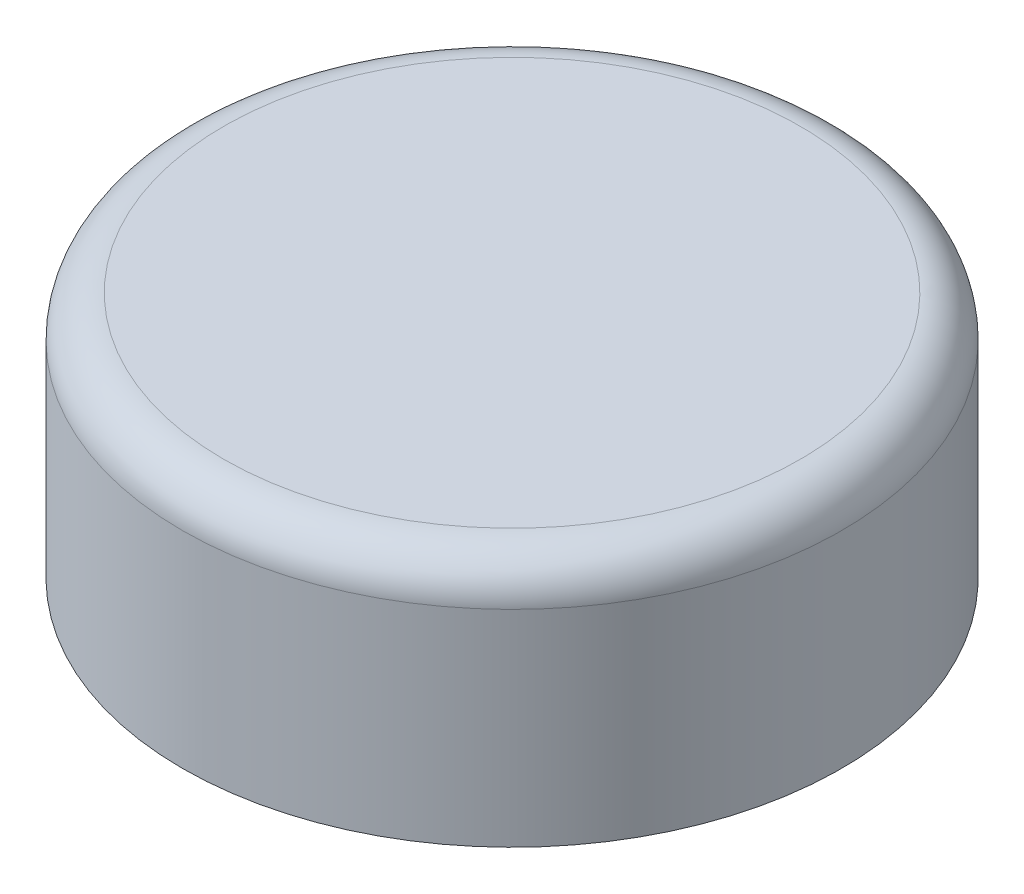
SolidWorks part; units mm, degrees
ref_plane "Front Plane" through (0, 0, 0) normal (0, 0, 1) x (1, 0, 0)
ref_plane "Top Plane" through (0, 0, 0) normal (0, 1, 0) x (1, 0, 0)
ref_plane "Right Plane" through (0, 0, 0) normal (1, 0, 0) x (0, 0, -1)
sketch "Sketch1" plane through (0, 0, 0) normal (0, 1, 0) x (1, 0, 0)
  circle A0 centre (0, 0) radius 40
  circle A1 centre (0, 0) radius 36
extrude "Boss-Extrude1" add sketch "Sketch1" along normal blind 30 contours A0
fillet "Fillet1" radius 5 1 edges at (0, 30, 40)
sketch "Sketch2" plane through (0, 0, 0) normal (0, -1, 0) x (1, 0, 0)
  circle A0 centre (0, 0) radius 36
extrude "Cut-Extrude1" cut sketch "Sketch2" against normal blind 25
